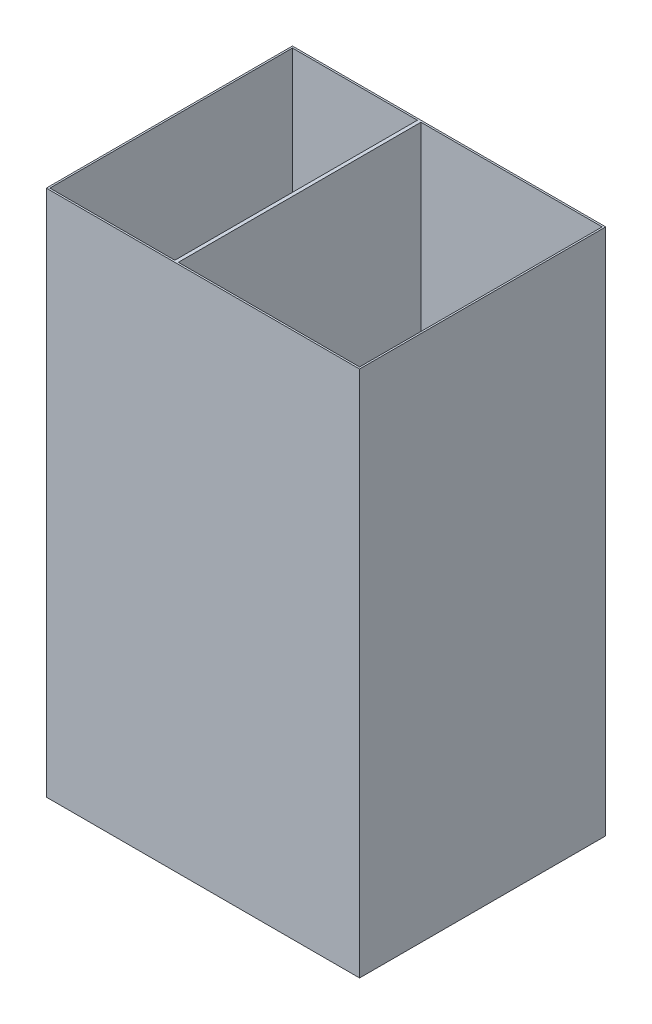
SolidWorks part; units mm, degrees
ref_plane "Plano frontal" through (0, 0, 0) normal (0, 0, 1) x (1, 0, 0)
ref_plane "Plano superior" through (0, 0, 0) normal (0, 1, 0) x (1, 0, 0)
ref_plane "Plano direito" through (0, 0, 0) normal (1, 0, 0) x (0, 0, -1)
ref_plane "Plano2" through (35.065, 0, 0) normal (1, 0, 0) x (0, 0, -1)
sketch "Esboço1" plane through (0, 0, 0) normal (0, 1, 0) x (1, 0, 0)
  line L0 (0, 40.7379) -> (0, -51.835) construction
  line L1 (-44.55, -35) -> (44.55, -35)
  line L2 (-44.55, -35) -> (-44.55, 35)
  line L3 (-44.55, 35) -> (44.55, 35)
  line L4 (44.55, -35) -> (44.55, 35)
  line L5 (-44.55, -35) -> (44.55, 35) construction
  line L6 (-44.55, 35) -> (44.55, -35) construction
  line L7 (-7.5, 34.5) -> (-7.5, -34.5)
  line L8 (-44.05, -34.5) -> (-8.5, -34.5)
  line L9 (-44.05, -34.5) -> (-44.05, 34.5)
  line L10 (-44.05, 34.5) -> (-8.5, 34.5)
  line L11 (44.05, -34.5) -> (44.05, 34.5)
  line L12 (-44.05, -34.5) -> (44.05, 34.5) construction
  line L13 (-44.05, 34.5) -> (44.05, -34.5) construction
  line L14 (-8.5, 34.5) -> (-8.5, -34.5)
  line L15 (-8.5, 35) -> (-8.5, -35) construction
  line L16 (-7.5, 35) -> (-7.5, -35) construction
  line L17 (-7.5, 34.5) -> (44.05, 34.5)
  line L18 (-7.5, -34.5) -> (44.05, -34.5)
  point P0 (0, 0)
  point P8 (0, 0)
  dimension "D1" = 70
  dimension "D2" = 89.1
  dimension "D3" = 69
  dimension "D4" = 88.1
  dimension "D5" = 7.5
extrude "Ressalto-extrusão1" add sketch "Esboço1" along normal blind 150
ref_plane "Plano3" through (0, 75, 0) normal (0, -1, 0) x (-1, 0, 0)
sketch "Esboço3" plane through (-7.5, 0, 0) normal (1, 0, 0) x (0, 0, -1)
  line L0 (0, -29.3971) -> (0, 77.9106) construction
  line L1 (67.6018, 75.0346) -> (15.5, 75.0346) construction
  line L2 (17.5, 75.0346) -> (15.5, 75.0346) construction
  line L5 (0, 78.5346) -> (0, 178.0004) construction
  line L6 (-15.5, 75.0346) -> (-20.3761, 75.0346) construction
  line L7 (-15.5, 75.0346) -> (-17.5, 75.0346) construction
  circle A3 centre (17.5, 75.0346) radius 2
  circle A4 centre (-17.5, 75.0346) radius 2
  circle A5 centre (0, 83.0346) radius 4.5
  point P9 (0, 75.0346)
  dimension "D1" = 8
  dimension "D2" = 9
extrude "Corte-extrusão1" cut sketch "Esboço3" against normal blind 1
